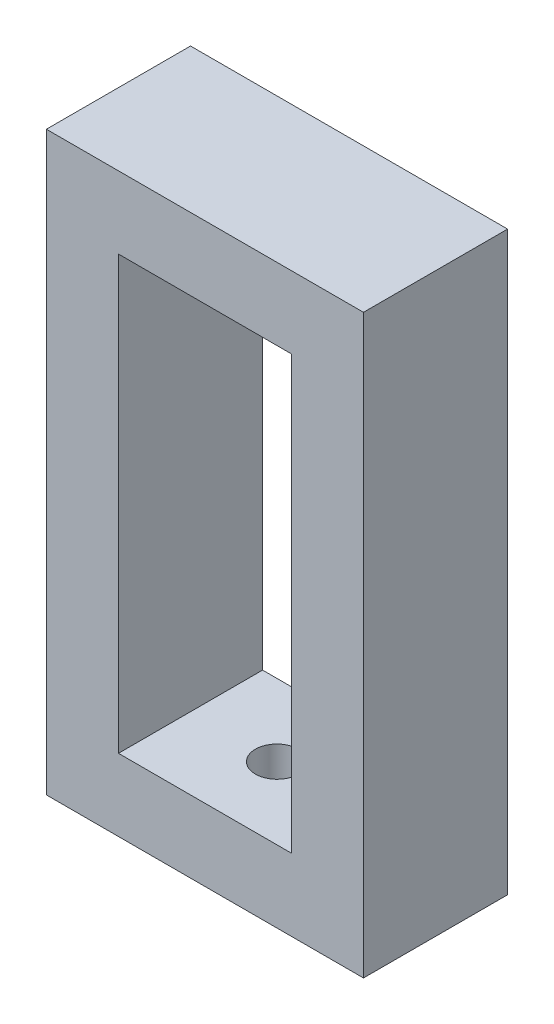
SolidWorks part; units mm, degrees
material "Brass"
ref_plane "Front Plane" through (0, 0, 0) normal (0, 0, 1) x (1, 0, 0)
ref_plane "Top Plane" through (0, 0, 0) normal (0, 1, 0) x (1, 0, 0)
ref_plane "Right Plane" through (0, 0, 0) normal (1, 0, 0) x (0, 0, -1)
sketch "Sketch1" plane through (0, 0, 0) normal (0, 0, 1) x (1, 0, 0)
  line L0 (0, 0) -> (22, 0)
  line L1 (22, 0) -> (22, 40)
  line L2 (22, 40) -> (0, 40)
  line L3 (0, 40) -> (0, 0)
  line L4 (5, 5) -> (17, 5)
  line L5 (17, 5) -> (17, 35)
  line L6 (17, 35) -> (5, 35)
  line L7 (5, 35) -> (5, 5)
extrude "Boss-Extrude1" add sketch "Sketch1" along normal blind 10
sketch "Sketch2" plane through (0, 0, 0) normal (0, 1, 0) x (1, 0, 0)
  circle A0 centre (11, -5) radius 1.5
  dimension "D1" = 3
extrude "Cut-Extrude1" cut sketch "Sketch2" against normal mid plane 30
